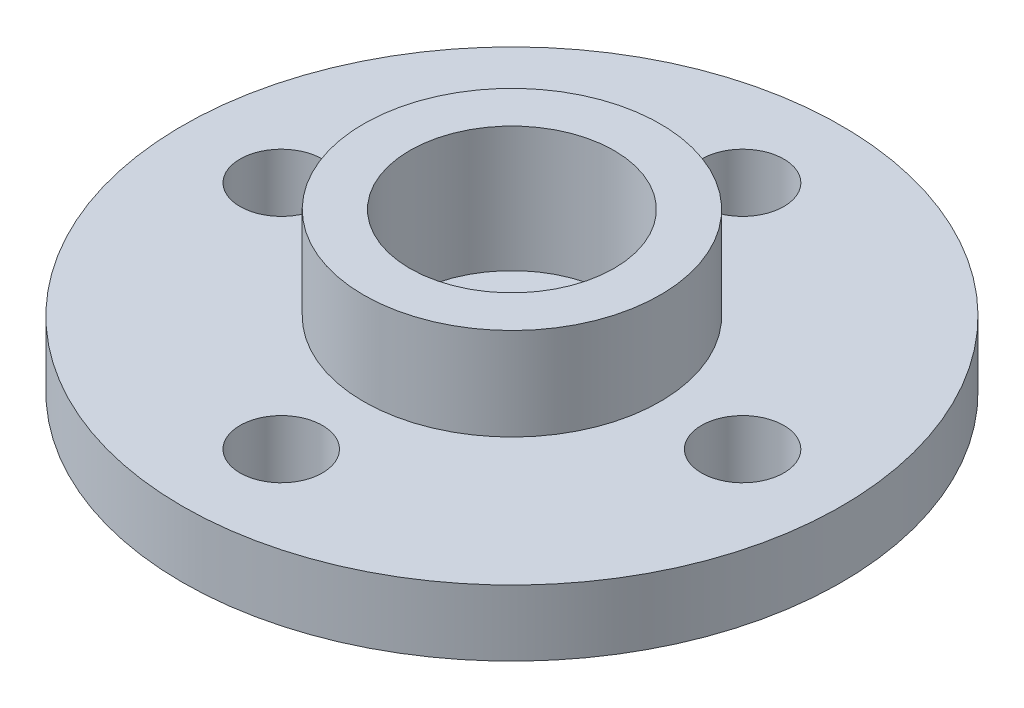
SolidWorks part; units mm, degrees
ref_plane "前视基准面" through (0, 0, 0) normal (0, 0, 1) x (1, 0, 0)
ref_plane "上视基准面" through (0, 0, 0) normal (0, 1, 0) x (1, 0, 0)
ref_plane "右视基准面" through (0, 0, 0) normal (1, 0, 0) x (0, 0, -1)
sketch "草图1" plane through (0, 0, 0) normal (0, 1, 0) x (1, 0, 0)
  circle A0 centre (0, 0) radius 10
  dimension "D1" = 20
extrude "凸台-拉伸1" add sketch "草图1" along normal blind 2
sketch "草图2" plane through (0, 2, 0) normal (0, 1, 0) x (1, 0, 0)
  circle A0 centre (0, 0) radius 4.5
  dimension "D1" = 9
extrude "凸台-拉伸2" add sketch "草图2" along normal blind 2.8
sketch "草图3" plane through (0, 4.8, 0) normal (0, 1, 0) x (1, 0, 0)
  circle A0 centre (0, 0) radius 3.1
  dimension "D1" = 6.2
extrude "切除-拉伸1" cut sketch "草图3" against normal blind 3.8
sketch "草图4" plane through (0, 1, 0) normal (0, 1, 0) x (1, 0, 0)
  circle A0 centre (0, 0) radius 1.6
  dimension "D1" = 3.2
extrude "切除-拉伸2" cut sketch "草图4" against normal up to next and the other way through all
sketch "草图5" plane through (0, 2, 0) normal (0, 1, 0) x (1, 0, 0)
  line L0 (-15.3981, 0) -> (14.4252, 0) construction
  line L1 (0, 14.5276) -> (0, -18.1496) construction
  circle A0 centre (-7, 0) radius 1.25
  circle A1 centre (0, 7) radius 1.25
  circle A2 centre (7, 0) radius 1.25
  circle A3 centre (0, -7) radius 1.25
  point P18 (0, 0)
  dimension "D1" = 2.5
  dimension "D2" = 7
  dimension "D3" = 4
extrude "切除-拉伸3" cut sketch "草图5" against normal up to next
